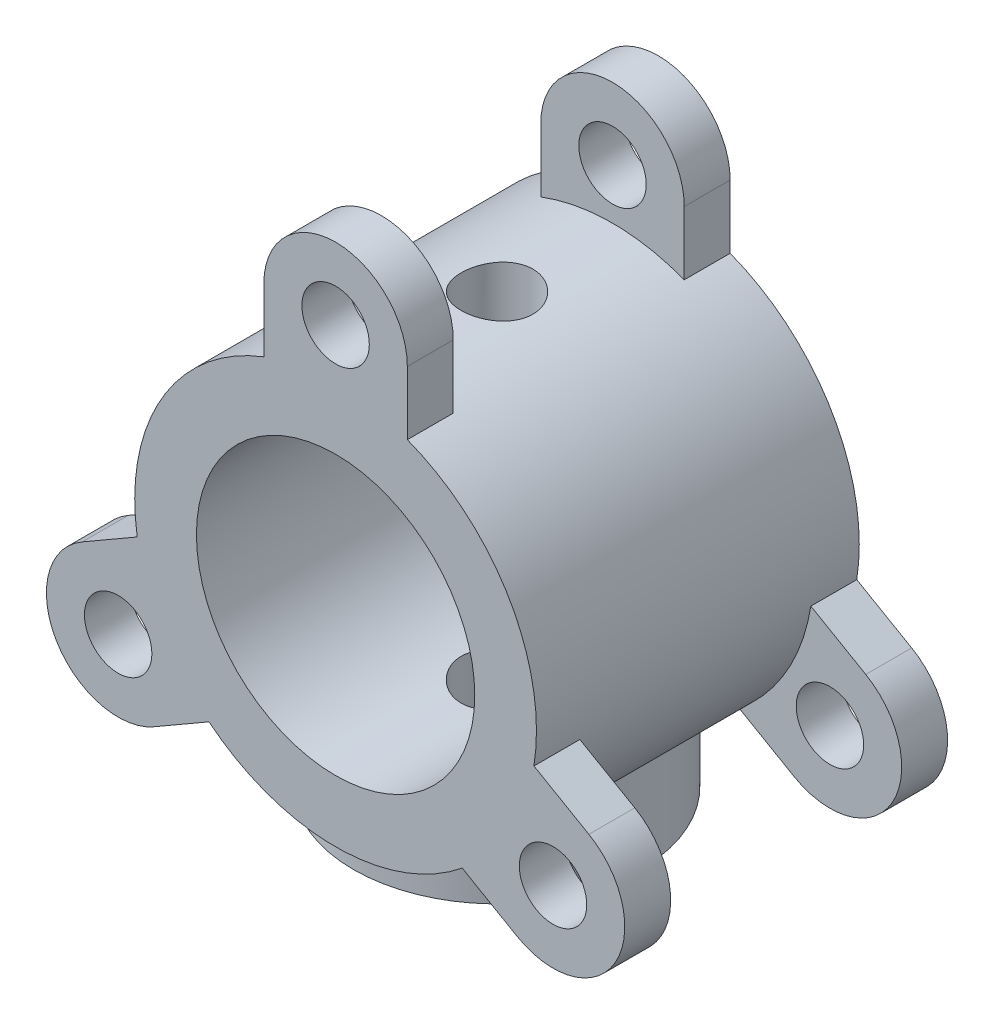
SolidWorks part; units mm, degrees
ref_plane "Front Plane" through (0, 0, 0) normal (0, 0, 1) x (1, 0, 0)
ref_plane "Top Plane" through (0, 0, 0) normal (0, 1, 0) x (1, 0, 0)
ref_plane "Right Plane" through (0, 0, 0) normal (1, 0, 0) x (0, 0, -1)
sketch "Sketch5" plane through (0, 0, 0) normal (0, 0, 1) x (1, 0, 0)
  circle A0 centre (0, 0) radius 97
  circle A1 centre (0, 0) radius 140
  dimension "D1" = 280
  dimension "D2" = 194
extrude "Boss-Extrude2" add sketch "Sketch5" along normal blind 225
sketch "Sketch6" plane through (0, 0, 225) normal (0, 0, 1) x (1, 0, 0)
  line L5 (50, 105.0274) -> (-50, 105.0274)
  line L6 (50, 105.0274) -> (50, 174.9726)
  line L8 (-50, 105.0274) -> (-50, 174.9726)
  line L9 (50, 105.0274) -> (-50, 174.9726) construction
  line L10 (50, 174.9726) -> (-50, 105.0274) construction
  circle A0 centre (0, 0) radius 140 construction
  arc A2 (50, 174.9726) -> (-50, 174.9726) centre (0, 175) ccw
  circle A3 centre (0, 175) radius 23.5
  point P0 (0, 140)
  dimension "D1" = 47
  dimension "D2" = 175
extrude "Boss-Extrude3" add sketch "Sketch6" against normal blind 32
pattern_circular "CirPattern1" count 3 over 360 about axis through (0, 0, 0) along (0, 0, 1) of "Boss-Extrude3"
ref_plane "Plane1" through (0, 0, 112.5) normal (0, 0, -1) x (-1, 0, 0)
mirror "Mirror1" about plane through (0, 0, 112.5) normal (0, 0, -1) of "CirPattern1", "Boss-Extrude3"
ref_plane "Plane3" through (0, -160, 0) normal (0, 1, 0) x (1, 0, 0)
sketch "Sketch7" plane through (0, -160, 0) normal (0, 1, 0) x (1, 0, 0)
  line L0 (0, 0) -> (0, -225) construction
  line L1 (-50, -225) -> (50, -225) construction
  circle A2 centre (0, -112.5) radius 100
  point P1 (0, 0)
  dimension "D1" = 200
  dimension "D2" = 112.5
extrude "Boss-Extrude4" add sketch "Sketch7" along normal up to next
sketch "Sketch9" plane through (0, -160, 0) normal (0, -1, 0) x (1, 0, 0)
  circle A0 centre (0, 112.5) radius 50
  dimension "D1" = 100
extrude "Cut-Extrude2" cut sketch "Sketch9" against normal blind 25
sketch "Sketch10" plane through (0, -135, 0) normal (0, -1, 0) x (1, 0, 0)
  circle A0 centre (0, 112.5) radius 25
  dimension "D1" = 50
extrude "Cut-Extrude3" cut sketch "Sketch10" against normal through all
sketch "Sketch11" plane through (0, -160, 0) normal (0, -1, 0) x (1, 0, 0)
  circle A0 centre (0, 187.5) radius 12
  circle A1 centre (0, 112.5) radius 25 construction
  dimension "D1" = 24
  dimension "D2" = 75
extrude "Cut-Extrude4" cut sketch "Sketch11" against normal blind 15
pattern_circular "CirPattern4" count 3 over 360 about axis through (0, 0, 112.5) along (0, 1, 0) of "Cut-Extrude4"
